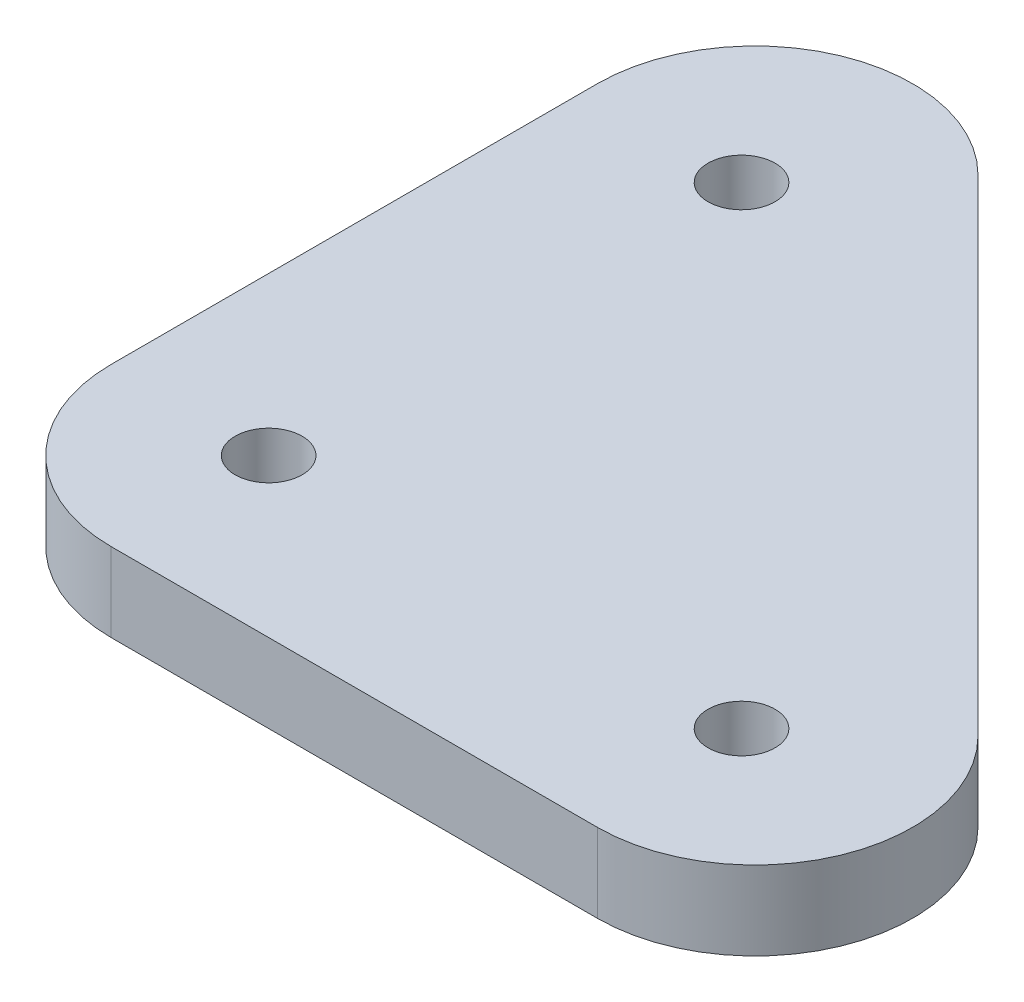
SolidWorks part; units mm, degrees
ref_plane "Front Plane" through (0, 0, 0) normal (0, 0, 1) x (1, 0, 0)
ref_plane "Top Plane" through (0, 0, 0) normal (0, 1, 0) x (1, 0, 0)
ref_plane "Right Plane" through (0, 0, 0) normal (1, 0, 0) x (0, 0, -1)
sketch "Sketch1" plane through (0, 0, 0) normal (0, 1, 0) x (1, 0, 0)
  line L0 (0, 10) -> (0, 40.8579)
  line L1 (17.0711, 47.9289) -> (47.9289, 17.0711)
  line L2 (40.8579, 0) -> (10, 0)
  arc A0 (47.9289, 17.0711) -> (40.8579, 0) centre (40.8579, 10) cw
  arc A1 (0, 40.8579) -> (17.0711, 47.9289) centre (10, 40.8579) cw
  arc A2 (0, 10) -> (10, 0) centre (10, 10) ccw
  circle A3 centre (10, 10) radius 2.125
  circle A4 centre (10, 40) radius 2.125
  circle A5 centre (40, 10) radius 2.125
  point P6 (65, 0)
  point P9 (0, 65)
  point P12 (0, 0)
  dimension "D3" = 10
  dimension "D4" = 10
  dimension "D9" = 4.25
  dimension "D10" = 4.25
  dimension "D11" = 4.25
  dimension "D1" = 65
  dimension "D2" = 65
  dimension "D5" = 10
  dimension "D6" = 10
  dimension "D7" = 10
  dimension "D8" = 10
  dimension "D12" = 40
  dimension "D13" = 40
extrude "Boss-Extrude1" add sketch "Sketch1" along normal blind 5
